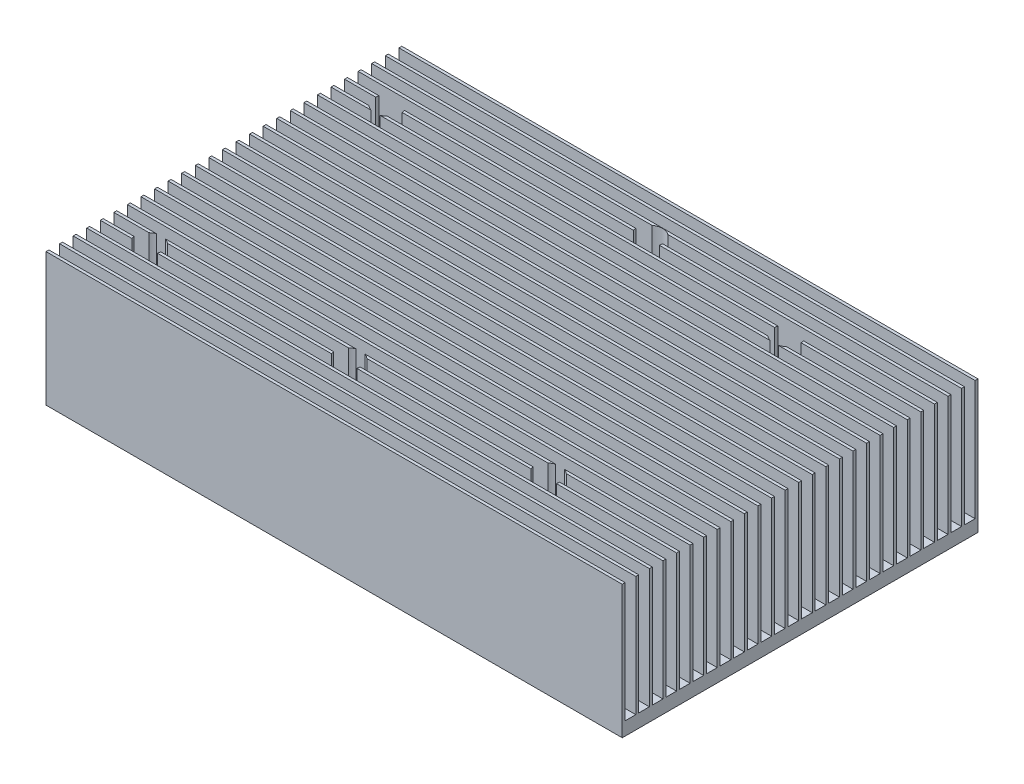
SolidWorks part; units mm, degrees
ref_plane "Front Plane" through (0, 0, 0) normal (0, 0, 1) x (1, 0, 0)
ref_plane "Top Plane" through (0, 0, 0) normal (0, 1, 0) x (1, 0, 0)
ref_plane "Right Plane" through (0, 0, 0) normal (1, 0, 0) x (0, 0, -1)
sketch "Sketch1" plane through (0, 0, 0) normal (1, 0, 0) x (0, 0, -1)
  line L0 (-40.13, 0) -> (-40.13, 30)
  line L1 (55, 0) -> (-55, 0) construction
  line L2 (-40.13, 30) -> (-39.48, 30)
  line L3 (-39.48, 30) -> (-39.48, 3)
  line L4 (-39.48, 3) -> (-37.0681, 3)
  line L5 (-37.0681, 3) -> (-37.0681, 30)
  line L6 (-37.0681, 30) -> (-36.4181, 30)
  line L7 (-36.4181, 30) -> (-36.4181, 3)
  line L8 (-36.4181, 3) -> (-34.0062, 3)
  line L9 (-34.0062, 3) -> (-34.0062, 30)
  line L10 (-34.0062, 30) -> (-33.3562, 30)
  line L11 (-33.3562, 30) -> (-33.3562, 3)
  line L12 (-33.3562, 3) -> (-30.9442, 3)
  line L13 (-30.9442, 3) -> (-30.9442, 30)
  line L14 (-30.9442, 30) -> (-30.2942, 30)
  line L15 (-30.2942, 30) -> (-30.2942, 3)
  line L16 (-30.2942, 3) -> (-27.8823, 3)
  line L17 (-27.8823, 3) -> (-27.8823, 30)
  line L18 (-27.8823, 30) -> (-27.2323, 30)
  line L19 (-27.2323, 30) -> (-27.2323, 3)
  line L20 (-27.2323, 3) -> (-24.8204, 3)
  line L21 (-24.8204, 3) -> (-24.8204, 30)
  line L22 (-24.8204, 30) -> (-24.1704, 30)
  line L23 (-24.1704, 30) -> (-24.1704, 3)
  line L24 (-24.1704, 3) -> (-21.7585, 3)
  line L25 (-21.7585, 3) -> (-21.7585, 30)
  line L26 (-21.7585, 30) -> (-21.1085, 30)
  line L27 (-21.1085, 30) -> (-21.1085, 3)
  line L28 (-21.1085, 3) -> (-18.6965, 3)
  line L29 (-18.6965, 3) -> (-18.6965, 30)
  line L30 (-18.6965, 30) -> (-18.0465, 30)
  line L31 (-18.0465, 30) -> (-18.0465, 3)
  line L32 (-18.0465, 3) -> (-15.6346, 3)
  line L33 (-15.6346, 3) -> (-15.6346, 30)
  line L34 (-15.6346, 30) -> (-14.9846, 30)
  line L35 (-14.9846, 30) -> (-14.9846, 3)
  line L36 (-14.9846, 3) -> (-12.5727, 3)
  line L37 (-12.5727, 3) -> (-12.5727, 30)
  line L38 (-12.5727, 30) -> (-11.9227, 30)
  line L39 (-11.9227, 30) -> (-11.9227, 3)
  line L40 (-11.9227, 3) -> (-9.5108, 3)
  line L41 (-9.5108, 3) -> (-9.5108, 30)
  line L42 (-9.5108, 30) -> (-8.8608, 30)
  line L43 (-8.8608, 30) -> (-8.8608, 3)
  line L44 (-8.8608, 3) -> (-6.4488, 3)
  line L45 (-6.4488, 3) -> (-6.4488, 30)
  line L46 (-6.4488, 30) -> (-5.7988, 30)
  line L47 (-5.7988, 30) -> (-5.7988, 3)
  line L48 (-5.7988, 3) -> (-3.3869, 3)
  line L49 (-3.3869, 3) -> (-3.3869, 30)
  line L50 (-3.3869, 30) -> (-2.7369, 30)
  line L51 (-2.7369, 30) -> (-2.7369, 3)
  line L52 (-2.7369, 3) -> (-0.325, 3)
  line L53 (-0.325, 3) -> (-0.325, 30)
  line L54 (-0.325, 30) -> (0.325, 30)
  line L55 (0.325, 30) -> (0.325, 3)
  line L56 (0.325, 3) -> (2.7369, 3)
  line L57 (2.7369, 3) -> (2.7369, 30)
  line L58 (2.7369, 30) -> (3.3869, 30)
  line L59 (3.3869, 30) -> (3.3869, 3)
  line L60 (3.3869, 3) -> (5.7988, 3)
  line L61 (5.7988, 3) -> (5.7988, 30)
  line L62 (5.7988, 30) -> (6.4488, 30)
  line L63 (6.4488, 30) -> (6.4488, 3)
  line L64 (6.4488, 3) -> (8.8608, 3)
  line L65 (8.8608, 3) -> (8.8608, 30)
  line L66 (8.8608, 30) -> (9.5108, 30)
  line L67 (9.5108, 30) -> (9.5108, 3)
  line L68 (9.5108, 3) -> (11.9227, 3)
  line L69 (11.9227, 3) -> (11.9227, 30)
  line L70 (11.9227, 30) -> (12.5727, 30)
  line L71 (12.5727, 30) -> (12.5727, 3)
  line L72 (12.5727, 3) -> (14.9846, 3)
  line L73 (14.9846, 3) -> (14.9846, 30)
  line L74 (14.9846, 30) -> (15.6346, 30)
  line L75 (15.6346, 30) -> (15.6346, 3)
  line L76 (15.6346, 3) -> (18.0465, 3)
  line L77 (18.0465, 3) -> (18.0465, 30)
  line L78 (18.0465, 30) -> (18.6965, 30)
  line L79 (18.6965, 30) -> (18.6965, 3)
  line L80 (18.6965, 3) -> (21.1085, 3)
  line L81 (21.1085, 3) -> (21.1085, 30)
  line L82 (21.1085, 30) -> (21.7585, 30)
  line L83 (21.7585, 30) -> (21.7585, 3)
  line L84 (21.7585, 3) -> (24.1704, 3)
  line L85 (24.1704, 3) -> (24.1704, 30)
  line L86 (24.1704, 30) -> (24.8204, 30)
  line L87 (24.8204, 30) -> (24.8204, 3)
  line L88 (24.8204, 3) -> (27.2323, 3)
  line L89 (27.2323, 3) -> (27.2323, 30)
  line L90 (27.2323, 30) -> (27.8823, 30)
  line L91 (27.8823, 30) -> (27.8823, 3)
  line L92 (27.8823, 3) -> (30.2942, 3)
  line L93 (30.2942, 3) -> (30.2942, 30)
  line L94 (30.2942, 30) -> (30.9442, 30)
  line L95 (30.9442, 30) -> (30.9442, 3)
  line L96 (30.9442, 3) -> (33.3562, 3)
  line L97 (33.3562, 3) -> (33.3562, 30)
  line L98 (33.3562, 30) -> (34.0062, 30)
  line L99 (34.0062, 30) -> (34.0062, 3)
  line L100 (34.0062, 3) -> (36.4181, 3)
  line L101 (36.4181, 3) -> (36.4181, 30)
  line L102 (36.4181, 30) -> (37.0681, 30)
  line L103 (37.0681, 30) -> (37.0681, 3)
  line L104 (37.0681, 3) -> (39.48, 3)
  line L105 (39.48, 3) -> (39.48, 30)
  line L106 (39.48, 30) -> (40.13, 30)
  line L107 (40.13, 30) -> (40.13, 3)
  line L108 (-40.13, 0) -> (40.13, 0)
  line L109 (40.13, 3) -> (42.5419, 3) [skipped]
  line L110 (40.13, 0) -> (40.13, 3)
  point P11 (0, 0)
  dimension "D1" = 0.65
  dimension "D2" = 80.26
  dimension "D4" = 30
  dimension "D5" = 3
  dimension "D3" = 26
extrude "Boss-Extrude1" add sketch "Sketch1" along normal blind 130
sketch "Sketch2" plane through (0, 3, 0) normal (0, 1, 0) x (1, 0, 0)
  line L0 (0, -55) -> (0, 55) construction
  line L1 (10, -27) -> (100, -27) construction
  line L2 (10, -27) -> (10, 27) construction
  line L3 (10, 27) -> (100, 27) construction
  line L4 (100, -27) -> (100, 27) construction
  line L5 (10, -27) -> (100, 27) construction
  line L6 (10, 27) -> (100, -27) construction
  line L8 (130, 30.9442) -> (0, 30.9442) construction
  circle A0 centre (10, 27) radius 3
  circle A1 centre (100, 27) radius 3
  circle A2 centre (65, 30.9442) radius 3
  circle A3 centre (10, -27) radius 3
  circle A4 centre (55, -27) radius 3
  circle A5 centre (100, -27) radius 3
  point P0 (55, 0)
  dimension "D3" = 6
  dimension "D1" = 90
  dimension "D2" = 54
  dimension "D4" = 10
extrude "Cut-Extrude1" cut sketch "Sketch2" along normal through all
hole_wizard "M3 Clearance Hole1" positions "3DSketch2" profile "Sketch4" hole size "M3" standard "ISO" end condition through all
sketch3d "3DSketch2"
  point P0 (10, 3, -27)
  point P3 (65, 3, -30.9442)
  point P6 (100, 3, -27)
  point P9 (10, 3, 27)
  point P12 (55, 3, 27)
  point P15 (100, 3, 27)
sketch "Sketch4" plane through (10, 3, -27) normal (1, 0, 0) x (0, 0, 1)
  line L0 (0, 0) -> (0, 3)
  line L1 (0, 3) -> (1.7, 3)
  line L2 (1.7, 3) -> (1.7, 0)
  line L5 (1.7, 0) -> (0, 0)
  line L11 (0, -6.35) -> (0, 107.95) construction
  dimension "Thru Hole Dia." = 3.4
  dimension "Thru Hole Depth" = 3
